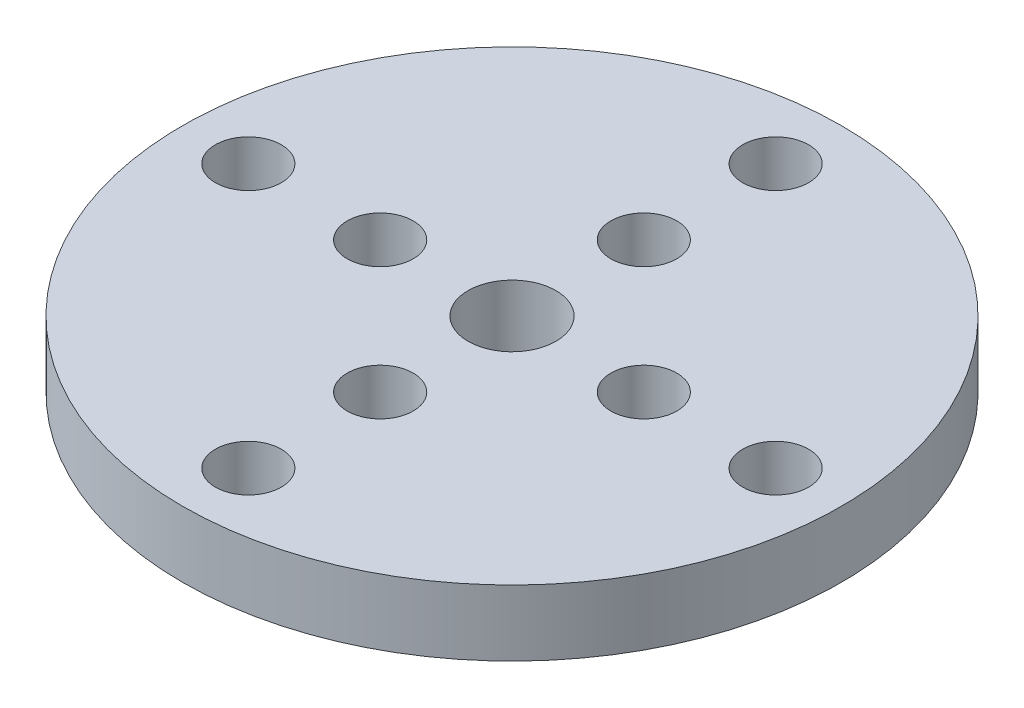
SolidWorks part; units mm, degrees
ref_plane "前视基准面" through (0, 0, 0) normal (0, 0, 1) x (1, 0, 0)
ref_plane "上视基准面" through (0, 0, 0) normal (0, 1, 0) x (1, 0, 0)
ref_plane "右视基准面" through (0, 0, 0) normal (1, 0, 0) x (0, 0, -1)
sketch "草图1" plane through (0, 0, 0) normal (0, 1, 0) x (1, 0, 0)
  line L0 (0, 0) -> (0, 18.2938) construction
  line L1 (0, 0) -> (19.7965, 0) construction
  circle A0 centre (0, 0) radius 6 construction
  circle A1 centre (0, 0) radius 12 construction
  circle A2 centre (0, 0) radius 2
  circle A3 centre (0, 6) radius 1.5
  circle A4 centre (6, 0) radius 1.5
  circle A5 centre (0, -6) radius 1.5
  circle A6 centre (-6, 0) radius 1.5
  circle A7 centre (0, 0) radius 15
  circle A8 centre (0, 12) radius 1.5
  circle A9 centre (12, 0) radius 1.5
  circle A10 centre (0, -12) radius 1.5
  circle A11 centre (-12, 0) radius 1.5
  point P16 (0, 0)
  point P28 (0, 0)
  dimension "D1" = 12
  dimension "D2" = 24
  dimension "D3" = 4
  dimension "D4" = 3
  dimension "D6" = 30
  dimension "D8" = 3
  dimension "D7" = 90
  dimension "D5" = 4
  dimension "D9" = 4
extrude "凸台-拉伸1" add sketch "草图1" along normal blind 3
